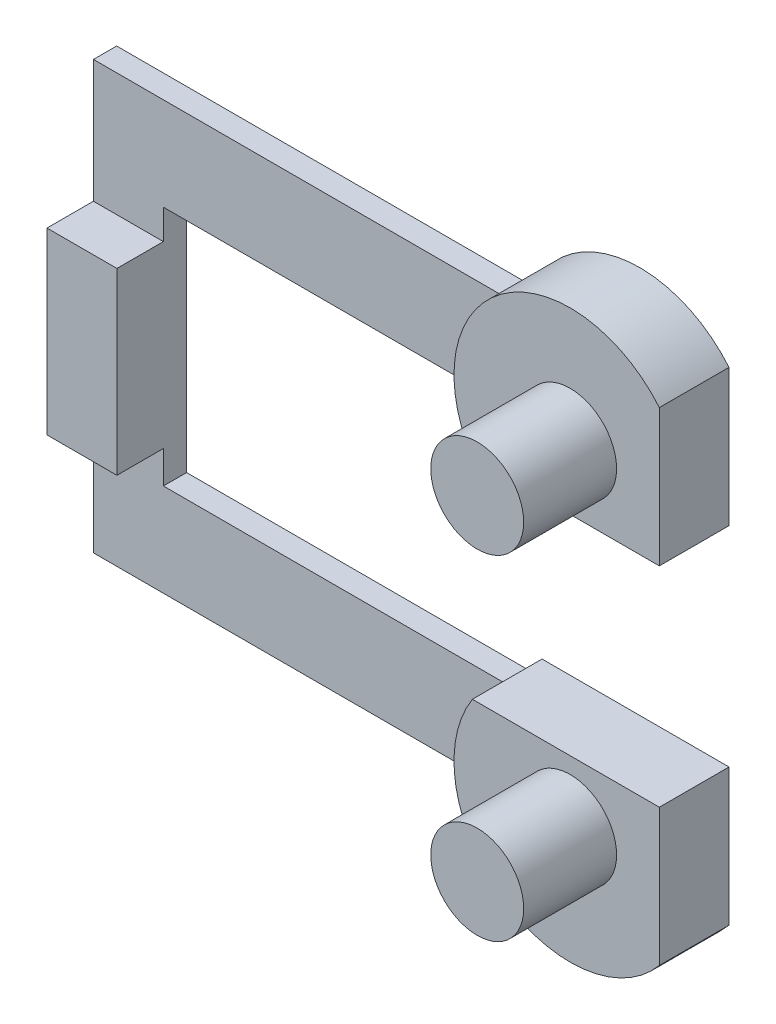
SolidWorks part; units mm, degrees
ref_plane "Спереди" through (0, 0, 0) normal (0, 0, 1) x (1, 0, 0)
ref_plane "Сверху" through (0, 0, 0) normal (0, 1, 0) x (1, 0, 0)
ref_plane "Справа" through (0, 0, 0) normal (1, 0, 0) x (0, 0, -1)
sketch "Skizze1" plane through (0, 0, 0) normal (0, 0, 1) x (1, 0, 0)
  circle A2 centre (50.1739, -0.1096) radius 2.5
  circle A3 centre (50.1739, 14.2904) radius 2.5
sketch "Skizze2" plane through (0, 0, 0) normal (0, 0, 1) x (1, 0, 0)
  circle A0 centre (50.1739, 14.2904) radius 2
  circle A1 centre (50.1739, -0.1096) radius 2
  dimension "D1" = 4
  dimension "D2" = 4
extrude "Aufsatz-Linear austragen1" add sketch "Skizze2" along normal blind 6
sketch "Skizze3" plane through (0, 0, 0) normal (0, 0, -1) x (-1, 0, 0)
  line L1 (-50.1739, 1.8904) -> (-27.6499, 1.8904)
  line L2 (-50.1739, 1.8904) -> (-50.1739, -2.1096)
  line L3 (-50.1739, -2.1096) -> (-27.6499, -2.1096)
  line L4 (-27.6499, 1.8904) -> (-27.6499, -2.1096)
  line L5 (-50.1739, 16.2904) -> (-27.6499, 16.2904)
  line L6 (-50.1739, 16.2904) -> (-50.1739, 12.2869)
  line L7 (-50.1739, 12.2869) -> (-27.6499, 12.2869)
  line L8 (-27.6499, 16.2904) -> (-27.6499, 12.2869)
  line L9 (-27.6499, 12.2869) -> (-30.661, 12.2869)
  line L10 (-27.6499, 12.2869) -> (-27.6499, 1.8904)
  line L11 (-27.6499, 1.8904) -> (-30.661, 1.8904)
  line L12 (-30.661, 12.2869) -> (-30.661, 1.8904)
  circle A0 centre (-50.1739, -0.1096) radius 2 construction
  circle A1 centre (-50.1739, 14.2904) radius 2 construction
  circle M1 centre (-50.1739, -0.1096) radius 2
extrude "Aufsatz-Linear austragen2" add sketch "Skizze3" along normal blind 1 contours L8 L5 L6 L7 | L7 L12 L1 L10 | L4 L1 L3 M1
sketch "Skizze4" plane through (0, 0, 0) normal (0, 0, -1) x (-1, 0, 0)
  circle A0 centre (-50.1739, -0.1096) radius 5
  circle A1 centre (-50.1739, 14.2904) radius 5
  dimension "D1" = 10
  dimension "D2" = 10
extrude "Aufsatz-Linear austragen3" add sketch "Skizze4" along normal blind 1
sketch "Skizze5" plane through (0, 0, 0) normal (0, 0, 1) x (1, 0, 0)
  circle A0 centre (50.1739, 14.2904) radius 5
  circle A1 centre (50.1739, -0.1096) radius 5
extrude "Aufsatz-Linear austragen4" add sketch "Skizze5" along normal blind 2
sketch "Skizze6" plane through (0, 0, 2) normal (0, 0, 1) x (1, 0, 0)
  line L0 (45.5928, 12.2869) -> (30.661, 12.2869) construction
  line L1 (43.661, 11.5869) -> (56.661, 11.5869)
  line L2 (43.661, 11.5869) -> (43.661, 2.5904)
  line L3 (43.661, 2.5904) -> (56.661, 2.5904)
  line L4 (56.661, 11.5869) -> (56.661, 2.5904)
  line L5 (45.5913, 1.8904) -> (30.661, 1.8904) construction
  line L6 (30.661, 12.2869) -> (30.661, 1.8904) construction
  dimension "D1" = 0.7
  dimension "D2" = 0.7
  dimension "D3" = 13
  dimension "D4" = 13
extrude "Schnitt-Linear austragen1" cut sketch "Skizze6" against normal blind 4.8
sketch "Skizze7" plane through (0, 0, 2) normal (0, 0, 1) x (1, 0, 0)
  line L1 (56.0358, 18.572) -> (54.0153, 18.572)
  line L2 (56.0358, 18.572) -> (56.0358, -4.2897)
  line L3 (56.0358, -4.2897) -> (54.0153, -4.2897)
  line L4 (54.0153, 18.572) -> (54.0153, -4.2897)
extrude "Schnitt-Linear austragen2" cut sketch "Skizze7" against normal blind 4.8
sketch "Skizze8" plane through (0, 0, 0) normal (0, 0, 1) x (1, 0, 0)
  line L0 (27.6499, 16.2904) -> (27.6499, -2.1096) construction
  line L1 (27.6499, 11.0027) -> (30.661, 11.0027)
  line L2 (27.6499, 11.0027) -> (27.6499, 3.2884)
  line L3 (27.6499, 3.2884) -> (30.661, 3.2884)
  line L4 (30.661, 11.0027) -> (30.661, 3.2884)
  line L5 (30.661, 12.2869) -> (30.661, 1.8904) construction
extrude "Aufsatz-Linear austragen5" add sketch "Skizze8" along normal blind 2
